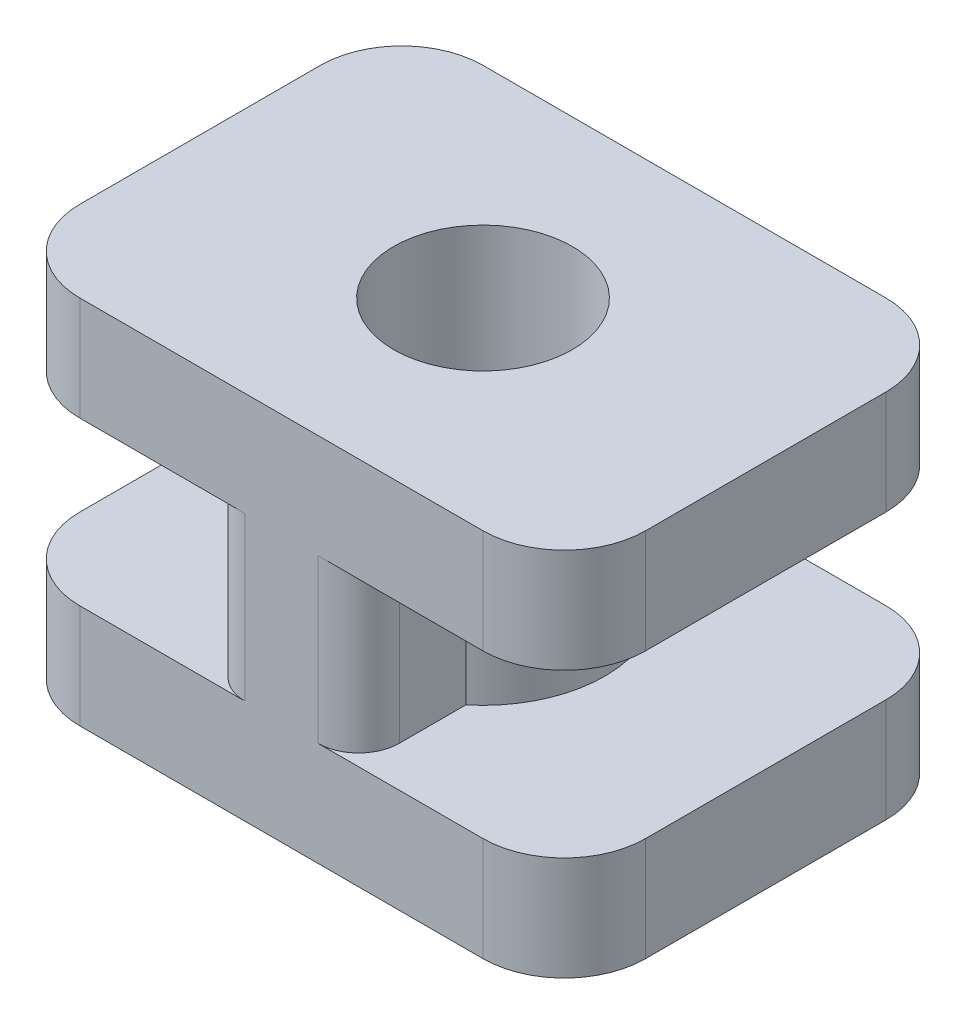
SolidWorks part; units mm, degrees
ref_plane "前基準面" through (0, 0, 0) normal (0, 0, 1) x (1, 0, 0)
ref_plane "上基準面" through (0, 0, 0) normal (0, 1, 0) x (1, 0, 0)
ref_plane "右基準面" through (0, 0, 0) normal (1, 0, 0) x (0, 0, -1)
ref_plane "平面1" through (0, 4.1656, 0) normal (0, -1, 0) x (1, 0, 0)
sketch "草圖1" plane through (0, 4.1656, 0) normal (0, -1, 0) x (1, 0, 0)
  line L0 (4.4196, 3.1496) -> (-4.4196, 3.1496)
  line L1 (-4.4196, 3.1496) -> (-4.4196, -3.1496)
  line L2 (-4.4196, -3.1496) -> (4.4196, -3.1496)
  line L3 (4.4196, -3.1496) -> (4.4196, 3.1496)
extrude "填料-伸長1" add sketch "草圖1" against normal blind 1.6256
sketch "草圖2" plane through (0, 4.1656, 0) normal (0, -1, 0) x (1, 0, 0)
  line L0 (-1.2065, 1.4742) -> (-1.2065, 3.1496)
  line L1 (-1.2065, 3.1496) -> (1.2065, 3.1496)
  line L2 (1.2065, 3.1496) -> (1.2065, 1.4742)
  arc A0 (1.2065, 1.4742) -> (-1.2065, 1.4742) centre (0, 0) cw
extrude "填料-伸長2" add sketch "草圖2" along normal blind 2.54
sketch "草圖3" plane through (0, 1.6256, 0) normal (0, -1, 0) x (1, 0, 0)
  line L0 (1.2065, 3.1496) -> (1.2065, -3.1496)
  line L1 (1.2065, -3.1496) -> (-4.4196, -3.1496)
  line L2 (-4.4196, -3.1496) -> (-4.4196, 3.1496)
  line L3 (-4.4196, 3.1496) -> (1.2065, 3.1496)
extrude "填料-伸長3" add sketch "草圖3" along normal blind 1.6256
sketch "草圖4" plane through (1.2065, 0, 0) normal (1, 0, 0) x (0, 0, -1)
  line L0 (-3.1496, 1.6256) -> (3.1496, 1.6256)
  line L1 (3.1496, 1.6256) -> (3.1496, 0)
  line L2 (3.1496, 0) -> (-3.1496, 0)
  line L3 (-3.1496, 0) -> (-3.1496, 1.6256)
extrude "填料-伸長4" add sketch "草圖4" along normal blind 3.2131
hole_wizard "M2.5 餘隙孔1" positions "草圖6" profile "草圖5" hole size "M2.5" standard "Ansi Metric"
sketch "草圖6" plane through (0, 5.7912, 0) normal (0, 1, 0) x (1, 0, 0)
  point P0 (0, 0)
sketch "草圖5" plane through (0, 5.7912, 0) normal (1, 0, 0) x (0, 0, 1)
  line L0 (0, 0) -> (0, 5.7912)
  line L1 (0, 5.7912) -> (1.397, 5.7912)
  line L2 (1.397, 5.7912) -> (1.397, 0)
  line L5 (1.397, 0) -> (0, 0)
  line L11 (0, -6.35) -> (0, 107.95) construction
  dimension "貫穿孔直徑" = 2.794
  dimension "貫穿孔深度" = 5.7912
fillet "圓角1" radius 0.635 2 edges at (1.2065, 2.8956, 3.1496) (-1.2065, 2.8956, 3.1496)
fillet "圓角2" radius 1.27 8 edges at (4.4196, 0.8128, -3.1496) (-4.4196, 0.8128, 3.1496) (-4.4196, 0.8128, -3.1496) (4.4196, 4.9784, -3.1496) (4.4196, 0.8128, 3.1496) (-4.4196, 4.9784, -3.1496) (4.4196, 4.9784, 3.1496) (-4.4196, 4.9784, 3.1496)
